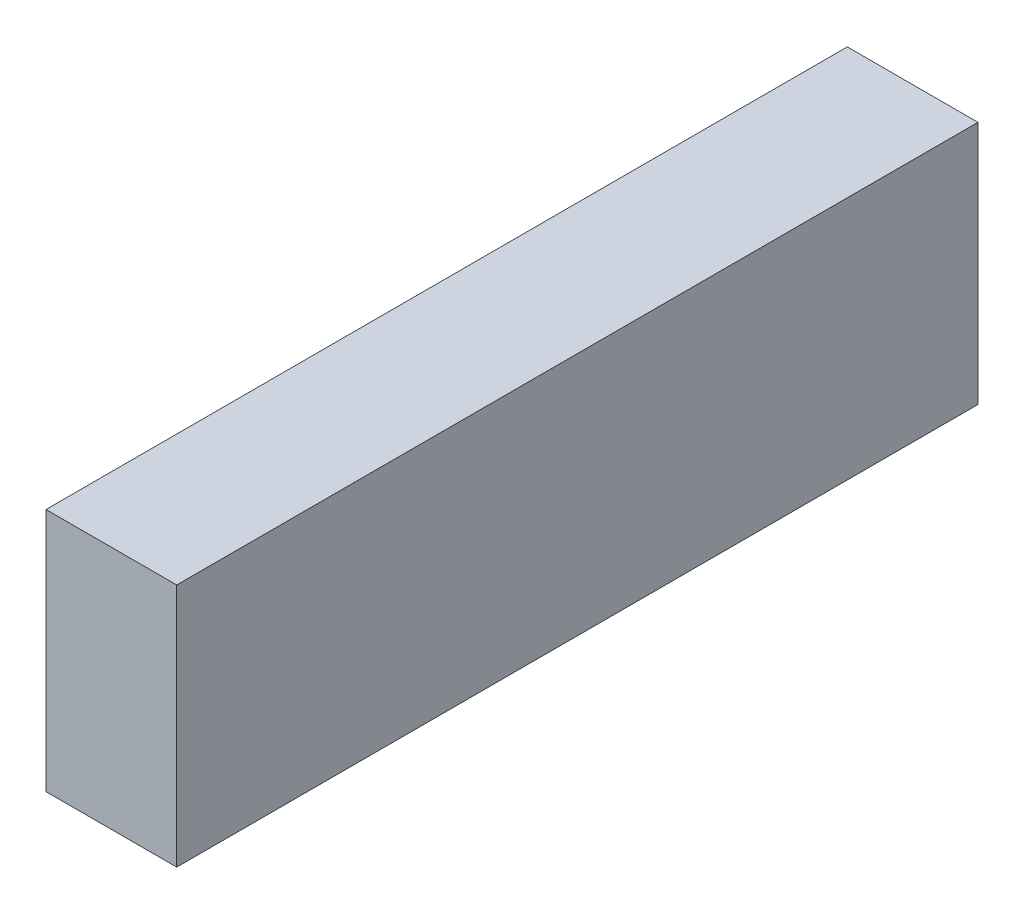
SolidWorks part; units mm, degrees
ref_plane "Piano frontale" through (0, 0, 0) normal (0, 0, 1) x (1, 0, 0)
ref_plane "Piano superiore" through (0, 0, 0) normal (0, 1, 0) x (1, 0, 0)
ref_plane "Piano destro" through (0, 0, 0) normal (1, 0, 0) x (0, 0, -1)
sketch "Schizzo1" plane through (0, 0, 0) normal (0, 0, 1) x (1, 0, 0)
  line L1 (11.5, -21.5) -> (-11.5, -21.5)
  line L2 (11.5, -21.5) -> (11.5, 21.5)
  line L3 (11.5, 21.5) -> (-11.5, 21.5)
  line L4 (-11.5, -21.5) -> (-11.5, 21.5)
  line L5 (11.5, -21.5) -> (-11.5, 21.5) construction
  line L6 (11.5, 21.5) -> (-11.5, -21.5) construction
  point P0 (0, 0)
  dimension "D1" = 43
  dimension "D2" = 23
extrude "Estrusione-Estrusione1" add sketch "Schizzo1" along normal blind 141
